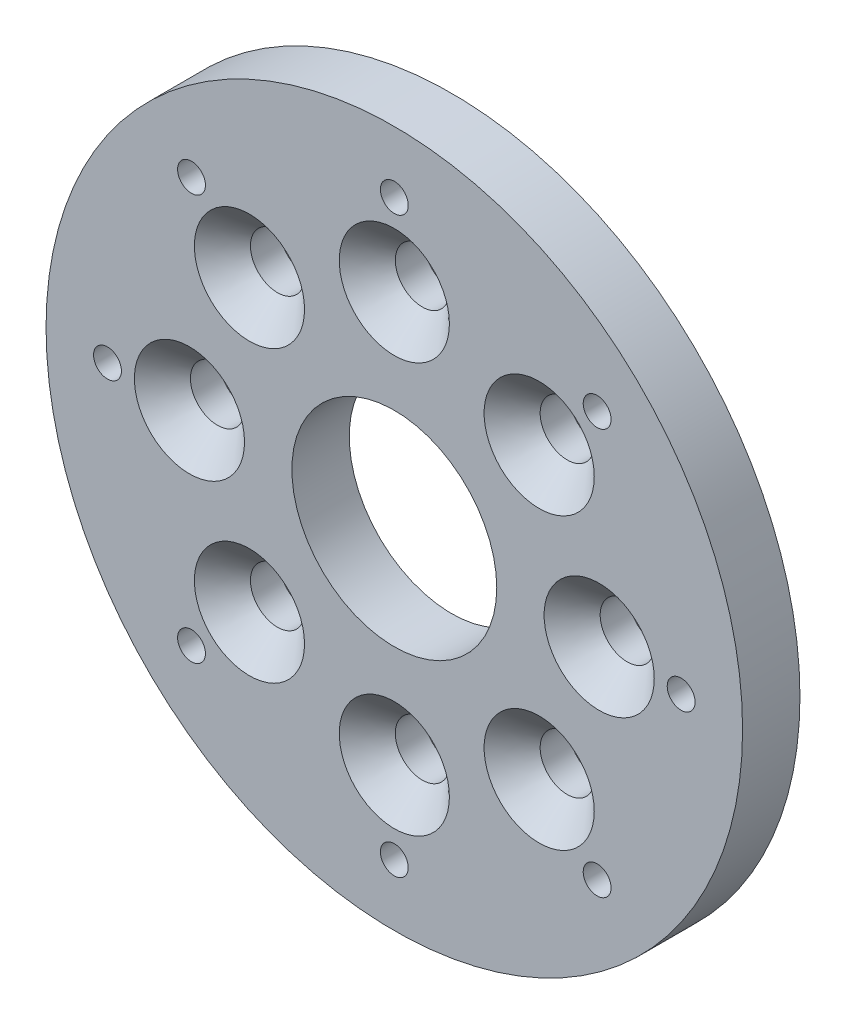
SolidWorks part; units mm, degrees
material "6063-T5"
ref_plane "Front" through (0, 0, 0) normal (0, 0, 1) x (1, 0, 0)
ref_plane "Top" through (0, 0, 0) normal (0, 1, 0) x (1, 0, 0)
ref_plane "Right" through (0, 0, 0) normal (1, 0, 0) x (0, 0, -1)
sketch "Croquis1" plane through (0, 0, 0) normal (0, 0, 1) x (1, 0, 0)
  circle A0 centre (0, 0) radius 42.5
  circle A1 centre (0, 0) radius 12.5
  dimension "D1" = 85
  dimension "D2" = 25
extrude "Saliente-Extruir1" add sketch "Croquis1" along normal blind 7
hole_wizard "Refrentado para tornillo tapón con cabeza plana de clavija de M61" positions "Croquis2" profile "Croquis4" countersink size "M6" standard "Ansi Metric"
sketch "Croquis2" plane through (0, 0, 7) normal (0, 0, 1) x (1, 0, 0)
  line L0 (0, -55) -> (0, 55) construction
  line L1 (0, 25) -> (0, -25) construction
  point P0 (0, 25)
  point P22 (17.6777, 17.6777)
  point P23 (25, 0)
  point P24 (17.6777, -17.6777)
  point P25 (0, -25)
  point P26 (-17.6777, -17.6777)
  point P27 (-25, 0)
  point P28 (-17.6777, 17.6777)
  dimension "D2" = 50
  dimension "D1" = 8
sketch "Croquis4" plane through (0, 25, 7) normal (1, 0, 0) x (0, -1, 0)
  line L0 (0, 0) -> (0, 11.9828)
  line L1 (0, 11.9828) -> (3.3, 10)
  line L2 (3.3, 10) -> (3.3, 3.42)
  line L3 (3.3, 3.42) -> (6.72, 0)
  line L5 (6.72, 0) -> (0, 0)
  line L6 (-3.3, 3.42) -> (-6.72, 0) construction
  line L10 (0, 11.9828) -> (-3.3, 10) construction
  line L11 (0, -6.35) -> (0, 107.95) construction
  dimension "Diámetro de taladro" = 6.6
  dimension "Profundidad de taladro" = 10
  dimension "Ángulo de avellanado cercano" = 13.44
  dimension "Ángulo de avellanado lejano" = 90
  dimension "Ángulo de perforador" = 118
hole_wizard "Refrentado para tornillo con cabeza troncocónica de M32" positions "Croquis5" profile "Croquis6" counterbore size "M3" standard "Ansi Metric"
sketch "Croquis5" plane through (0, 0, 0) normal (0, 0, -1) x (-1, 0, 0)
  line L0 (0, 55) -> (0, -55) construction
  line L1 (0, 35) -> (0, -35) construction
  point P0 (0, 35)
  point P16 (24.7487, 24.7487)
  point P17 (35, 0)
  point P18 (24.7487, -24.7487)
  point P19 (0, -35)
  point P20 (-24.7487, -24.7487)
  point P21 (-35, 0)
  point P22 (-24.7487, 24.7487)
  dimension "D2" = 70
  dimension "D1" = 8
sketch "Croquis6" plane through (0, 35, 0) normal (1, 0, 0) x (0, 1, 0)
  line L0 (0, 0) -> (0, 11.0215)
  line L1 (0, 11.0215) -> (1.7, 10)
  line L2 (1.7, 10) -> (1.7, 2.4)
  line L3 (1.7, 2.4) -> (3.5, 2.4)
  line L4 (3.5, 2.4) -> (3.5, 0)
  line L5 (3.5, 0) -> (0, 0)
  line L10 (0, 11.0215) -> (-1.7, 10) construction
  line L11 (0, -6.35) -> (0, 107.95) construction
  dimension "Diámetro de taladro" = 3.4
  dimension "Profundidad de taladro" = 10
  dimension "Diámetro de refrentado" = 7
  dimension "Profundidad de refrentado" = 2.4
  dimension "Ángulo de perforador" = 118
